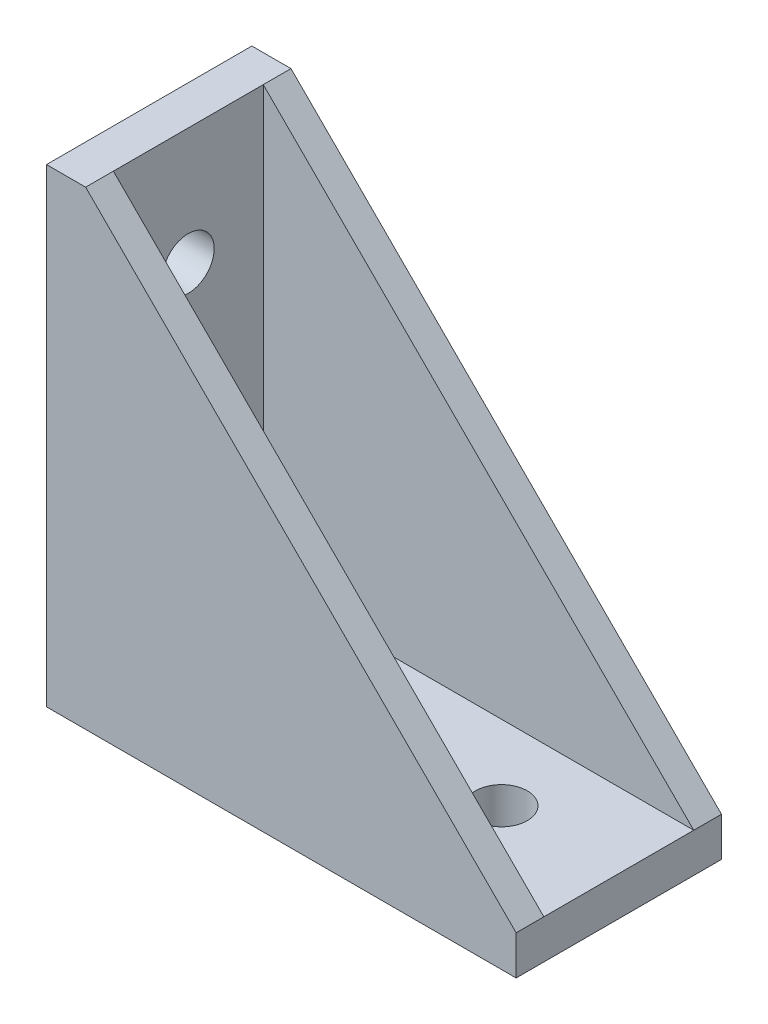
SolidWorks part; units mm, degrees
ref_plane "Front Plane" through (0, 0, 0) normal (0, 0, 1) x (1, 0, 0)
ref_plane "Top Plane" through (0, 0, 0) normal (0, 1, 0) x (1, 0, 0)
ref_plane "Right Plane" through (0, 0, 0) normal (1, 0, 0) x (0, 0, -1)
ref_plane "Plane_zm16_66" through (0, 0, -16.66) normal (0, 0, 1) x (1, 0, 0)
sketch "Sketch1" plane through (0, 0, -16.66) normal (0, 0, 1) x (1, 0, 0)
  line L0 (0, 0) -> (76.2, 0)
  line L1 (76.2, 0) -> (76.2, 6.35)
  line L2 (76.2, 6.35) -> (6.35, 76.2)
  line L3 (6.35, 76.2) -> (0, 76.2)
  line L4 (0, 76.2) -> (0, 0)
extrude "Body" add sketch "Sketch1" along normal blind 33.32
ref_plane "Plane_z12_16" through (0, 0, 12.16) normal (0, 0, 1) x (1, 0, 0)
sketch "Sketch2" plane through (0, 0, 12.16) normal (0, 0, 1) x (1, 0, 0)
  line L0 (6.35, 6.35) -> (86.2, 6.35)
  line L1 (86.2, 6.35) -> (6.35, 86.2)
  line L2 (6.35, 86.2) -> (6.35, 6.35)
extrude "Pocket" cut sketch "Sketch2" against normal blind 24.32
ref_plane "Plane_y6_35" through (0, 6.35, 0) normal (0, 1, 0) x (1, 0, 0)
sketch "Sketch3" plane through (0, 6.35, 0) normal (0, 1, 0) x (1, 0, 0)
  circle A0 centre (19.05, 0) radius 4.2
  circle A1 centre (57.15, 0) radius 4.2
extrude "HolesX" cut sketch "Sketch3" against normal blind 6.35
ref_plane "Plane_x6_35" through (6.35, 0, 0) normal (1, 0, 0) x (0, 0, -1)
sketch "Sketch4" plane through (6.35, 0, 0) normal (1, 0, 0) x (0, 0, -1)
  circle A0 centre (0, 19.05) radius 4.2
  circle A1 centre (0, 57.15) radius 4.2
extrude "HolesY" cut sketch "Sketch4" against normal blind 6.35
